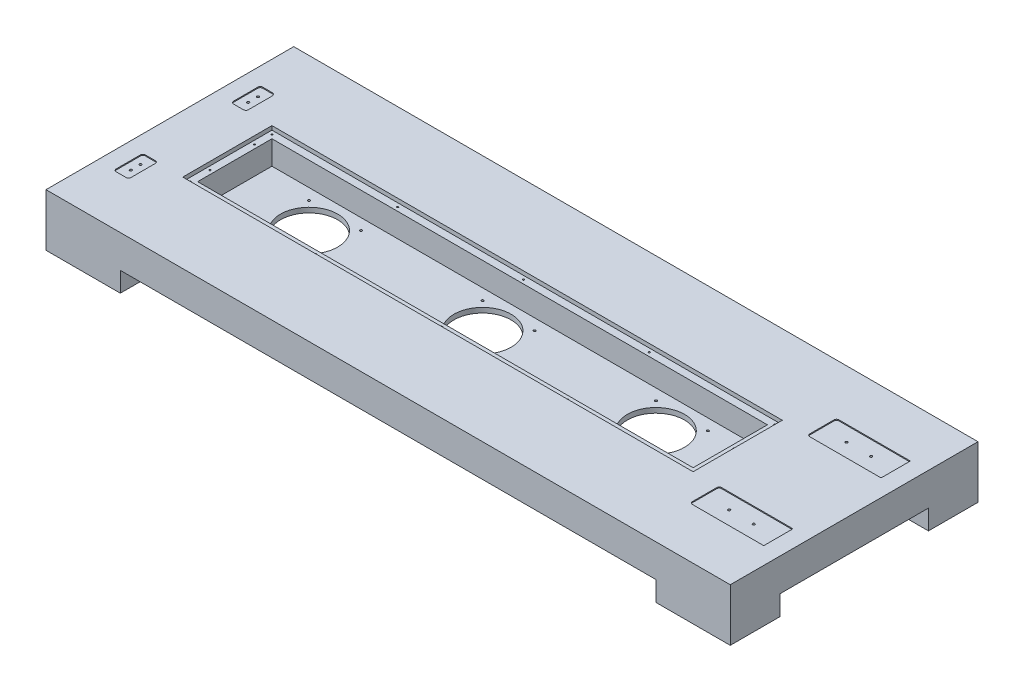
SolidWorks part; units mm, degrees
ref_plane "Front Plane" through (0, 0, 0) normal (0, 0, 1) x (1, 0, 0)
ref_plane "Top Plane" through (0, 0, 0) normal (0, 1, 0) x (1, 0, 0)
ref_plane "Right Plane" through (0, 0, 0) normal (1, 0, 0) x (0, 0, -1)
sketch "Sketch1" plane through (0, 0, 0) normal (0, 1, 0) x (1, 0, 0)
  line L1 (-750, 250) -> (750, 250)
  line L2 (-750, 250) -> (-750, -250)
  line L3 (-750, -250) -> (750, -250)
  line L4 (750, 250) -> (750, -250)
  line L5 (-750, 250) -> (750, -250) construction
  line L6 (-750, -250) -> (750, 250) construction
  point P0 (0, 0)
  dimension "D1" = 1500
  dimension "D2" = 500
sketch "Sketch19" plane through (0, 0, 0) normal (0, 1, 0) x (1, 0, 0)
  line L2 (-515, 90) -> (-515, -90)
  line L4 (-500, 75) -> (-500, -75)
  line L6 (-500, -75) -> (500, -75)
  line L8 (-515, -90) -> (515, -90)
  line L10 (-515, 90) -> (515, 90)
  line L12 (-500, 75) -> (500, 75)
  line L14 (0, 90) -> (0, -90) construction
  line L16 (500, 75) -> (500, -75)
  line L18 (515, 90) -> (515, -90)
  point P3 (-500, 0)
  dimension "D1" = 15
  dimension "D2" = 15
  dimension "D3" = 15
  dimension "D4" = 15
  dimension "D5" = 1000
  dimension "D6" = 150
extrude "Boss-Extrude2" add sketch "Sketch19" along normal blind 48 separate body
sketch "Sketch22" plane through (0, 0, 0) normal (0, 1, 0) x (1, 0, 0)
  line L1 (-515, 90) -> (515, 90)
  line L2 (-515, 90) -> (-515, -90)
  line L3 (-515, -90) -> (515, -90)
  line L4 (515, 90) -> (515, -90)
  line L5 (-515, 90) -> (515, -90) construction
  line L6 (-515, -90) -> (515, 90) construction
extrude "Boss-Extrude3" add sketch "Sketch22" against normal blind 10
sketch "Sketch23" plane through (0, 0, 0) normal (0, 1, 0) x (1, 0, 0)
  line L0 (-515, -90) -> (515, -90) construction
  line L1 (-750, 250) -> (750, 250)
  line L2 (-750, 250) -> (-750, -250)
  line L3 (-750, -250) -> (750, -250)
  line L4 (750, 250) -> (750, -250)
  line L5 (-515, 90) -> (-515, -90) construction
  line L6 (515, 90) -> (-515, 90) construction
  line L7 (515, -90) -> (515, 90) construction
  line L8 (-515, -90) -> (515, -90)
  line L9 (-515, 90) -> (-515, -90)
  line L10 (515, 90) -> (-515, 90)
  line L11 (515, -90) -> (515, 90)
extrude "Boss-Extrude4" add sketch "Sketch23" along normal offset from surface 8 and the other way up to surface (10 mm away) up to face at (0, 48, 0) offset beyond the face yes other way up to face at (0, -10, 0)
sketch "Sketch25" plane through (0, 0, 0) normal (0, -1, 0) x (1, 0, 0)
  line L0 (376.7104, 95) -> (506.8132, 123.2951) construction
  line L1 (376.7104, 133.9838) -> (510.7651, 84.6333) construction
  line L6 (-515, 90) -> (515, 90) construction
  line L8 (521.7058, 80.9826) -> (521.6427, 137.9826)
  line L9 (376.7104, 90) -> (520.9741, 90)
  line L10 (371.7104, 133.9838) -> (371.7104, 95)
  line L11 (520.6818, 138.8932) -> (376.6818, 138.9837)
  arc A0 (371.7104, 95) -> (376.7104, 90) centre (376.7104, 95) ccw
  arc A8 (520.9741, 90) -> (521.7058, 80.9826) centre (510.7651, 84.6333) ccw
  arc A10 (376.6818, 138.9837) -> (371.7104, 133.9838) centre (376.7104, 133.9838) ccw
  arc A11 (521.6427, 137.9826) -> (520.6818, 138.8932) centre (506.8132, 123.2951) ccw
  point P2 (443.2788, 109.4775)
  dimension "D5" = 5
  dimension "D2" = 5
  dimension "D1" = 144
  dimension "D4" = 57
sketch "Sketch26" plane through (0, 0, 0) normal (0, 1, 0) x (1, 0, 0)
  line L0 (-500, -75) -> (-515, -90) construction
  line L1 (-515, 90) -> (-500, 75) construction
  line L2 (500, -75) -> (515, -90) construction
  line L5 (500, 75) -> (515, 90) construction
  circle A2 centre (-507.5, -82.5) radius 1.65
  circle A3 centre (-507.5, 82.5) radius 1.65
  point P4 (-507.5, -82.5)
  point P15 (507.5, -82.5)
  point P16 (507.5, 82.5)
  dimension "D1" = 3.3
  dimension "D3" = 3.3
extrude "Cut-Extrude6" cut sketch "Sketch26" against normal blind 20 from surface at 48 starting at face at (0, 48, 0)
pattern_linear "LPattern1" count 5 spacing 253.75 along (1, 0, 0) of "Cut-Extrude6"
sketch "Sketch27" plane through (0, 0, 0) normal (0, 1, 0) x (1, 0, 0)
  line L0 (-500, 0) -> (-515, 0) construction
  line L1 (-500, 75) -> (-500, -75) construction
  line L2 (-515, -90) -> (-515, 90) construction
  line L3 (500, 0) -> (515, 0) construction
  line L4 (500, -75) -> (500, 75) construction
  line L5 (515, 90) -> (515, -90) construction
  line L6 (-507.5, 82.5) -> (-507.5, -82.5) construction
  circle A0 centre (507.5, 0) radius 1.65
  circle A2 centre (-507.5, 47.5033) radius 1.65
  circle A3 centre (-507.5, -42.3945) radius 1.65
  dimension "D1" = 3.3
  dimension "D2" = 3.3
  dimension "D3" = 3.3
sketch "Sketch28" plane through (0, 0, 0) normal (0, 1, 0) x (1, 0, 0)
  line L0 (0, 0) -> (57.7, 0) construction
  line L1 (-52.5, 52.5) -> (52.5, 52.5) construction
  line L2 (-52.5, 52.5) -> (-52.5, -52.5) construction
  line L3 (-52.5, -52.5) -> (52.5, -52.5) construction
  line L4 (52.5, 52.5) -> (52.5, -52.5) construction
  line L5 (-52.5, 52.5) -> (52.5, -52.5) construction
  line L6 (-52.5, -52.5) -> (52.5, 52.5) construction
  circle A0 centre (-52.5, 52.5) radius 2.3
  circle A1 centre (52.5, 52.5) radius 2.3
  circle A2 centre (52.5, -52.5) radius 2.3
  circle A3 centre (-52.5, -52.5) radius 2.3
  circle A4 centre (0, 0) radius 57.7
  point P2 (0, 0)
  dimension "D3" = 4.6
  dimension "D4" = 4.6
  dimension "D5" = 4.6
  dimension "D6" = 4.6
  dimension "D7" = 57.7
  dimension "D1" = 105
  dimension "D2" = 105
extrude "Cut-Extrude7" cut sketch "Sketch28" against normal through all both and the other way through all
pattern_linear "LPattern2" count 2 spacing 350 along (-1, 0, 0) count 2 spacing 350 along (1, 0, 0) of "Cut-Extrude7"
extrude "Cut-Extrude8" cut sketch "Sketch27" against normal blind 20 from surface at 48 starting at face at (253.75, 48, -84.15)
sketch "Sketch30" plane through (0, 0, 0) normal (0, -1, 0) x (1, 0, 0)
  line L0 (566.5, -147.92) -> (715.5, -88.92) construction
  line L1 (566.5, -88.92) -> (715.5, -147.92) construction
  line L2 (566.5, -93.92) -> (566.5, -88.92) construction
  line L3 (566.5, -88.92) -> (571.5, -88.92) construction
  line L4 (571.5, -147.92) -> (566.5, -147.92) construction
  line L5 (566.5, -147.92) -> (566.5, -142.92) construction
  line L6 (571.5, -147.92) -> (714.5, -147.92)
  line L7 (0, 0) -> (750, 0) construction
  line L8 (715.5, -146.92) -> (715.5, -89.92)
  line L10 (566.5, -93.92) -> (566.5, -142.92)
  line L11 (714.5, -88.92) -> (571.5, -88.92)
  line L12 (750, -250) -> (750, 250) construction
  line L14 (0, 0) -> (0, -118.42) construction
  line L15 (566.5, -118.42) -> (0, -118.42) construction
  arc A0 (715.5, -89.92) -> (714.5, -88.92) centre (714.5, -89.92) ccw
  arc A1 (714.5, -147.92) -> (715.5, -146.92) centre (714.5, -146.92) ccw
  arc A9 (566.5, -142.92) -> (571.5, -147.92) centre (571.5, -142.92) ccw
  arc A10 (571.5, -88.92) -> (566.5, -93.92) centre (571.5, -93.92) ccw
  dimension "D1" = 5
  dimension "D2" = 5
  dimension "D5" = 88.92
  dimension "D6" = 566.5
  dimension "D3" = 1
  dimension "D4" = 49
  dimension "D8" = 144
extrude "Cut-Extrude9" cut sketch "Sketch30" along normal blind 2 from surface at -56 starting at face at (0, 56, 0)
mirror "Mirror1" about plane through (0, 0, 0) normal (0, 0, 1) of "Cut-Extrude9"
sketch "Sketch32" plane through (0, 0, 0) normal (0, 1, 0) x (1, 0, 0)
  line L4 (-566.5, 118.42) -> (566.5, 118.42) construction
  line L5 (-591.5, 147.92) -> (-571.5, 147.92)
  line L6 (-596.5, 142.92) -> (-596.5, 93.92)
  line L7 (-591.5, 88.92) -> (-571.5, 88.92)
  line L8 (-566.5, 142.92) -> (-566.5, 93.92)
  line L9 (566.5, 93.92) -> (566.5, 142.92) construction
  arc A4 (-566.5, 142.92) -> (-571.5, 147.92) centre (-571.5, 142.92) ccw
  arc A5 (-566.5, 93.92) -> (-571.5, 88.92) centre (-571.5, 93.92) cw
  arc A6 (-596.5, 93.92) -> (-591.5, 88.92) centre (-591.5, 93.92) ccw
  arc A7 (-596.5, 142.92) -> (-591.5, 147.92) centre (-591.5, 142.92) cw
  point P6 (-566.5, 147.92)
  point P11 (-596.5, 88.92)
  point P14 (-596.5, 147.92)
  dimension "D2" = 20
  dimension "D3" = 5
  dimension "D1" = 49
  dimension "D4" = 1133
extrude "Cut-Extrude10" cut sketch "Sketch32" against normal blind 2 from surface at 56 starting at face at (0, 56, 0)
mirror "Mirror2" about plane through (0, 0, 0) normal (0, 0, 1) of "Cut-Extrude10"
sketch "Sketch33" plane through (0, 0, 0) normal (0, 1, 0) x (1, 0, 0)
  line L0 (-581.5, 147.92) -> (-581.5, 88.92) construction
  line L1 (-571.5, 147.92) -> (-591.5, 147.92) construction
  line L2 (-591.5, 88.92) -> (-571.5, 88.92) construction
  line L3 (-581.5, -88.92) -> (-581.5, -147.92) construction
  line L4 (-591.5, -88.92) -> (-571.5, -88.92) construction
  line L5 (-571.5, -147.92) -> (-591.5, -147.92) construction
  line L6 (566.5, 118.42) -> (715.5, 118.42) construction
  line L7 (566.5, 93.92) -> (566.5, 142.92) construction
  line L8 (715.5, 146.92) -> (715.5, 89.92) construction
  line L9 (566.5, -118.42) -> (715.5, -118.42) construction
  line L10 (566.5, -93.92) -> (566.5, -142.92) construction
  line L11 (715.5, -146.92) -> (715.5, -89.92) construction
  circle A0 centre (-581.5, 108.58) radius 2.35
  circle A1 centre (-581.5, -108.59) radius 2.35
  circle A2 centre (-581.5, 128.25) radius 2.35
  circle A3 centre (-581.5, -128.26) radius 2.35
  circle A4 centre (616.17, -118.42) radius 2.35
  circle A5 centre (665.84, -118.42) radius 2.35
  circle A6 centre (616.17, 118.42) radius 2.35
  circle A7 centre (665.84, 118.42) radius 2.35
  dimension "D1" = 4.7
  dimension "D2" = 4.7
  dimension "D3" = 4.7
  dimension "D8" = 4.7
  dimension "D11" = 4.7
  dimension "D12" = 4.7
  dimension "D13" = 4.7
  dimension "D14" = 4.7
  dimension "D4" = 19.67
  dimension "D5" = 19.67
  dimension "D6" = 19.67
  dimension "D7" = 19.67
  dimension "D9" = 49.67
  dimension "D10" = 49.67
extrude "Cut-Extrude11" cut sketch "Sketch33" against normal through all both and the other way through all
sketch "Sketch34" plane through (0, 0, 0) normal (0, 1, 0) x (1, 0, 0)
  line L0 (-596.5, -118.42) -> (-631, -118.42) construction
  line L1 (-596.5, -142.92) -> (-596.5, -93.92) construction
  line L2 (750, -250) -> (-750, -250) construction
  line L3 (-631, -250) -> (-821.8308, -250)
  line L4 (-631, -250) -> (-631, 290.53)
  line L5 (-631, 290.53) -> (-821.8308, 290.53)
  line L6 (-821.8308, -250) -> (-821.8308, 290.53)
  dimension "D1" = 34.5
extrude "Cut-Extrude12" cut sketch "Sketch34" along normal through all both and the other way through all
sketch "Sketch29" plane through (0, 0, 0) normal (0, 1, 0) x (1, 0, 0)
  line L1 (-631, -250) -> (-481, -250)
  line L2 (-631, -250) -> (-631, -150)
  line L3 (-631, -150) -> (-481, -150)
  line L4 (-481, -250) -> (-481, -150)
  line L5 (-631, 250) -> (-481, 250)
  line L6 (-631, 250) -> (-631, 150)
  line L7 (-631, 150) -> (-481, 150)
  line L8 (-481, 250) -> (-481, 150)
  line L9 (750, -250) -> (600, -250)
  line L10 (750, -250) -> (750, -150)
  line L11 (750, -150) -> (600, -150)
  line L12 (600, -250) -> (600, -150)
  line L13 (750, 250) -> (600, 250)
  line L14 (750, 250) -> (750, 150)
  line L15 (750, 150) -> (600, 150)
  line L16 (600, 250) -> (600, 150)
  dimension "D1" = 150
  dimension "D2" = 100
  dimension "D3" = 150
  dimension "D4" = 100
  dimension "D5" = 150
  dimension "D6" = 100
  dimension "D7" = 100
  dimension "D8" = 150
extrude "Boss-Extrude5" add sketch "Sketch29" against normal blind 50
